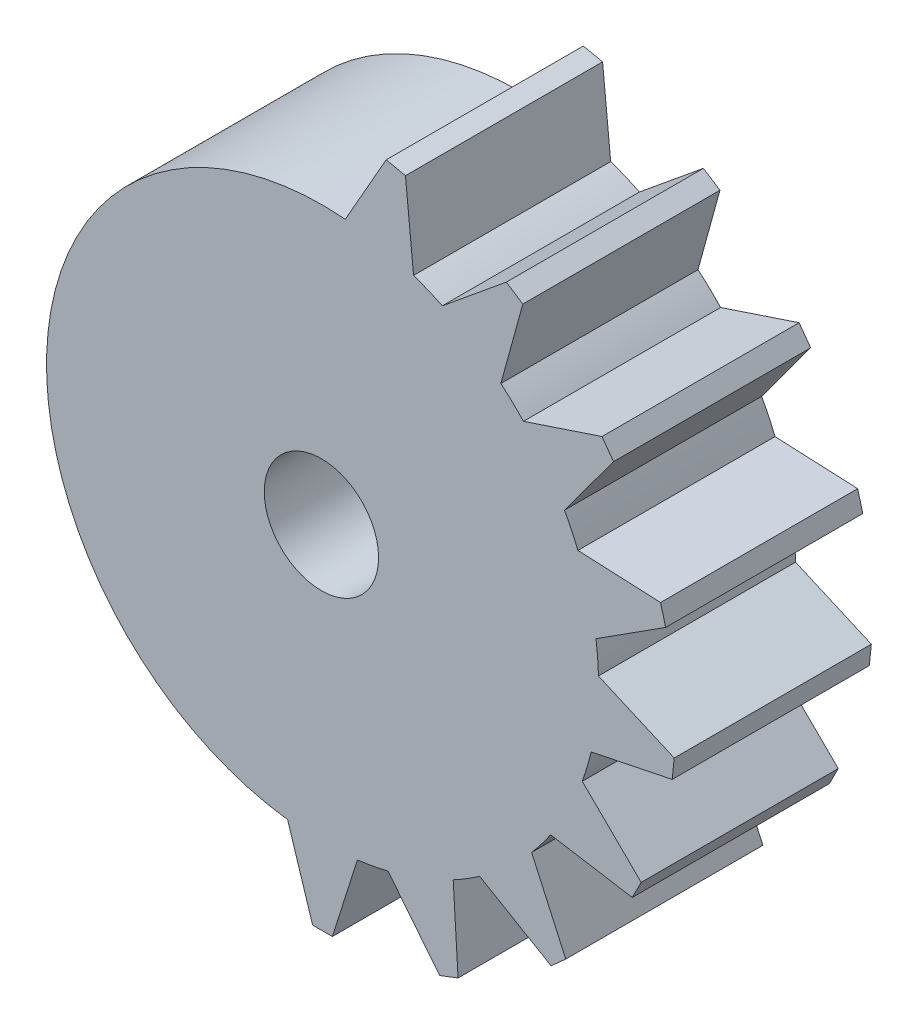
SolidWorks part; units mm, degrees
ref_plane "Front Plane" through (0, 0, 0) normal (0, 0, 1) x (1, 0, 0)
ref_plane "Top Plane" through (0, 0, 0) normal (0, 1, 0) x (1, 0, 0)
ref_plane "Right Plane" through (0, 0, 0) normal (1, 0, 0) x (0, 0, -1)
sketch "Sketch1" plane through (0, 0, 0) normal (0, 0, 1) x (1, 0, 0)
  line L3 (0.2026, -1.4358) -> (1.4439, 0.1324)
  circle A0 centre (0.0279, 0.0352) radius 7
  arc A4 (1.4439, 0.1324) -> (0.2026, -1.4358) centre (0, 0) ccw
  dimension "D1" = 14
extrude "Boss-Extrude1" add sketch "Sketch1" along normal blind 5
sketch "Sketch3" plane through (0, 0, 0) normal (0, 0, -1) x (-1, 0, 0)
  line L0 (0.8571, -6.9086) -> (-0.9129, -6.9086)
  line L1 (-0.9129, -6.9086) -> (-0.2779, -8.9086)
  line L2 (-0.2779, -8.9086) -> (0.2221, -8.9086)
  line L3 (0.2221, -8.9086) -> (0.8571, -6.9086)
  circle A2 centre (-0.0279, 0.0352) radius 7 construction
  point P10 (-0.0279, -8.9086)
  point P11 (-0.0279, -6.9086)
  dimension "D1" = 1.77
  dimension "D2" = 0.5
  dimension "D4" = 2
extrude "Boss-Extrude2" add sketch "Sketch3" against normal up to surface (5 mm away) up to face at (7.0279, 0.0352, 5)
pattern_circular "CirPattern3" count 9 every 21 about axis through (0.0279, 0.0352, 0) along (0, 0, 1) of "Boss-Extrude2"
sketch "Sketch5" plane through (0, 0, 5) normal (0, 0, 1) x (1, 0, 0)
  circle A0 centre (0, 0) radius 1.45
  dimension "D1" = 2.9
extrude "Cut-Extrude1" cut sketch "Sketch5" against normal offset from surface (3.5 mm away) 1.5 up to face at (4.6425, -0.4498, 0)
